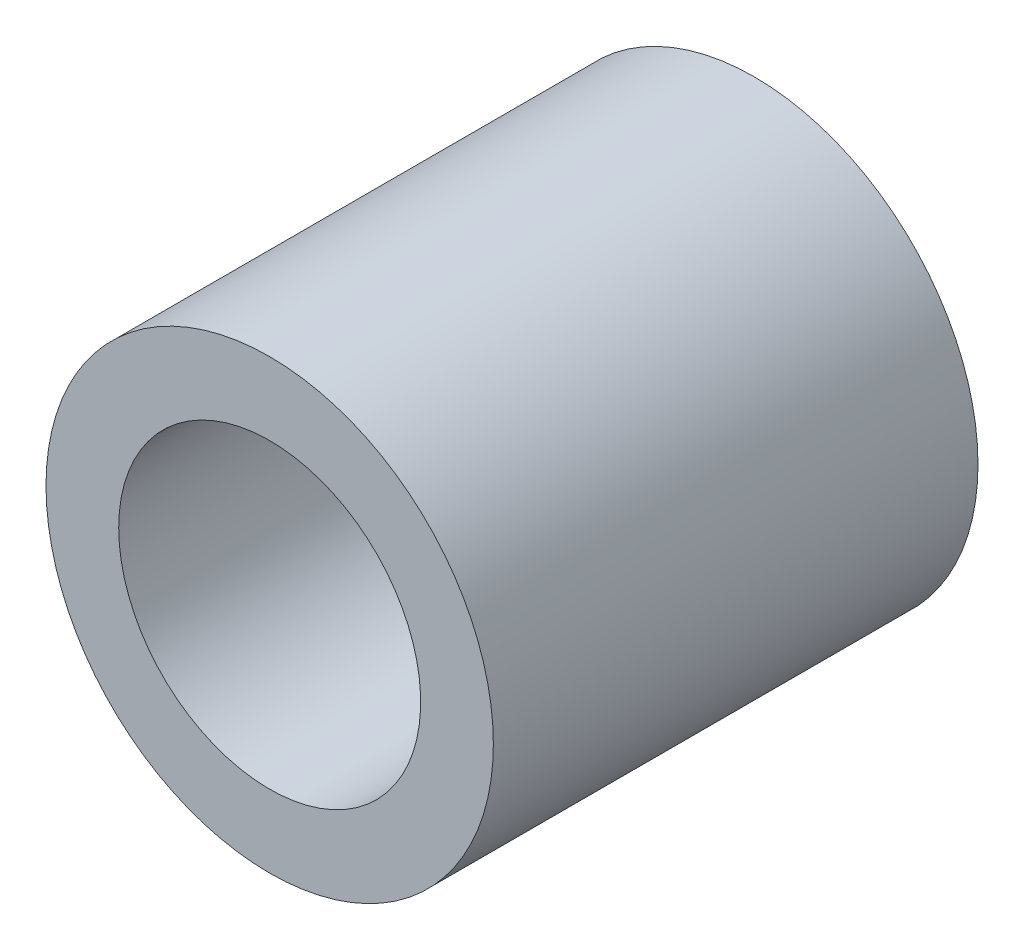
SolidWorks part; units mm, degrees
ref_plane "Front" through (0, 0, 0) normal (0, 0, 1) x (1, 0, 0)
ref_plane "Top" through (0, 0, 0) normal (0, 1, 0) x (1, 0, 0)
ref_plane "Right" through (0, 0, 0) normal (1, 0, 0) x (0, 0, -1)
sketch "Esquisse1" plane through (0, 0, 0) normal (0, 0, 1) x (1, 0, 0)
  circle A0 centre (0, 0) radius 4.05
  circle A1 centre (0, 0) radius 6
  dimension "D1" = 8.1
  dimension "D2" = 12
extrude "Boss.-Extru.1" add sketch "Esquisse1" along normal blind 13
